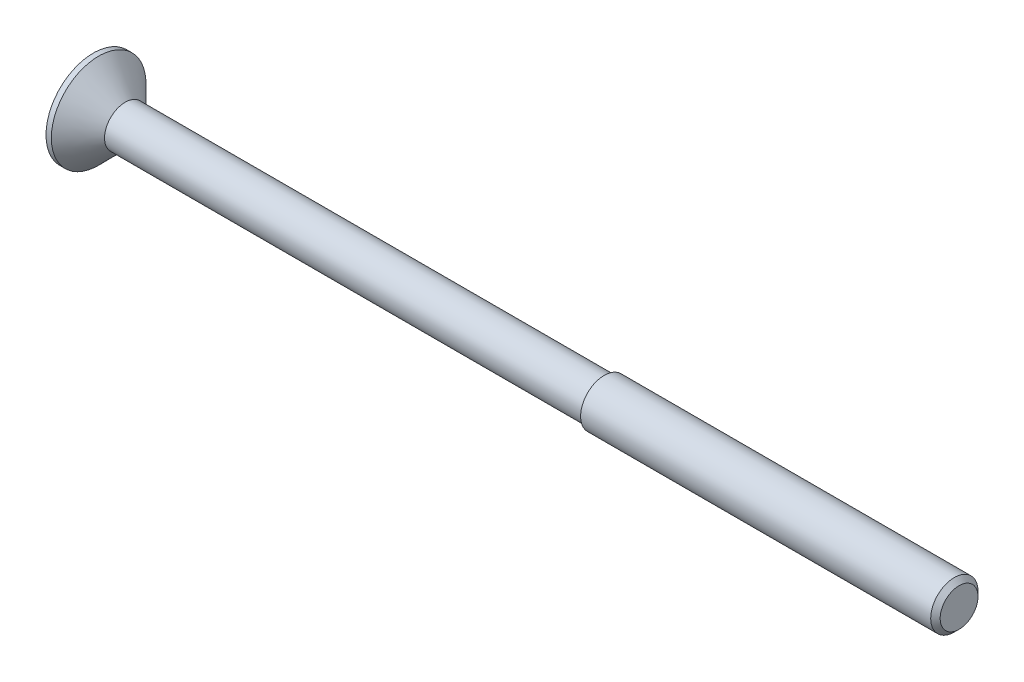
SolidWorks part; units mm, degrees
material "Acier allié"
ref_plane "Plan de face" through (0, 0, 0) normal (0, 0, 1) x (1, 0, 0)
ref_plane "Plan de dessus" through (0, 0, 0) normal (0, 1, 0) x (1, 0, 0)
ref_plane "Plan de droite" through (0, 0, 0) normal (1, 0, 0) x (0, 0, -1)
sketch "Esquisse1" plane through (0, 0, 0) normal (0, 0, 1) x (1, 0, 0)
  line L0 (0, 0) -> (157.0958, 0) construction
  line L1 (0, 0) -> (0, 4)
  line L2 (0, 4) -> (0.45, 4)
  line L3 (0.45, 4) -> (2.7, 1.75)
  line L4 (2.7, 1.75) -> (43.2, 1.75)
  line L5 (43.2, 1.75) -> (43.2, 2)
  line L6 (43.2, 2) -> (72.8, 2)
  line L7 (72.8, 2) -> (73.2, 1.6)
  line L8 (73.2, 1.6) -> (73.2, 0)
  line L9 (73.2, 0) -> (0, 0)
  dimension "D1" = 8
  dimension "D2" = 3.5
  dimension "D3" = 45
  dimension "D4" = 4
  dimension "D5" = 45
  dimension "D6" = 30
  dimension "D7" = 73.2
  dimension "D8" = 0.4
  dimension "D9" = 2.7
revolve "Révolution1" add sketch "Esquisse1" angle 360 about L0
cosmetic thread "Représentation de filetage1" parameters "D1"=30, "D2"=3.22
sketch "Esquisse2" plane through (0, 0, 0) normal (0, 0, 1) x (1, 0, 0)
  line L0 (0, 0) -> (0, 2.5)
  line L1 (0, 4) -> (0, -4) construction
  line L2 (0, 2.5) -> (0.5, 2)
  line L3 (0.5, 2) -> (2.5, 1.0028)
  line L4 (0, 0) -> (3.6061, 0) construction
  line L5 (2.5, 1.0028) -> (2.5, 0)
  line L6 (2.5, 0) -> (0, 0)
  dimension "D1" = 5
  dimension "D2" = 26.5
  dimension "D3" = 45
  dimension "D4" = 0.5
  dimension "D5" = 2.5
extrude "Enlèv. mat.-Extru.1" cut sketch "Esquisse2" against normal mid plane 1.4
pattern_circular "Répétition circulaire1" count 4 over 360 about axis through (0, 0, 0) along (1, 0, 0) of "Enlèv. mat.-Extru.1"
sketch "Esquisse3" plane through (0, 0, 0) normal (-1, 0, 0) x (0, 0, 1)
  circle A0 centre (0, 0) radius 1.25
  dimension "D1" = 2.5
extrude "Enlèv. mat.-Extru.2" cut sketch "Esquisse3" against normal up to surface (2.5 mm away) up to face at (2.5, 0, 0)
